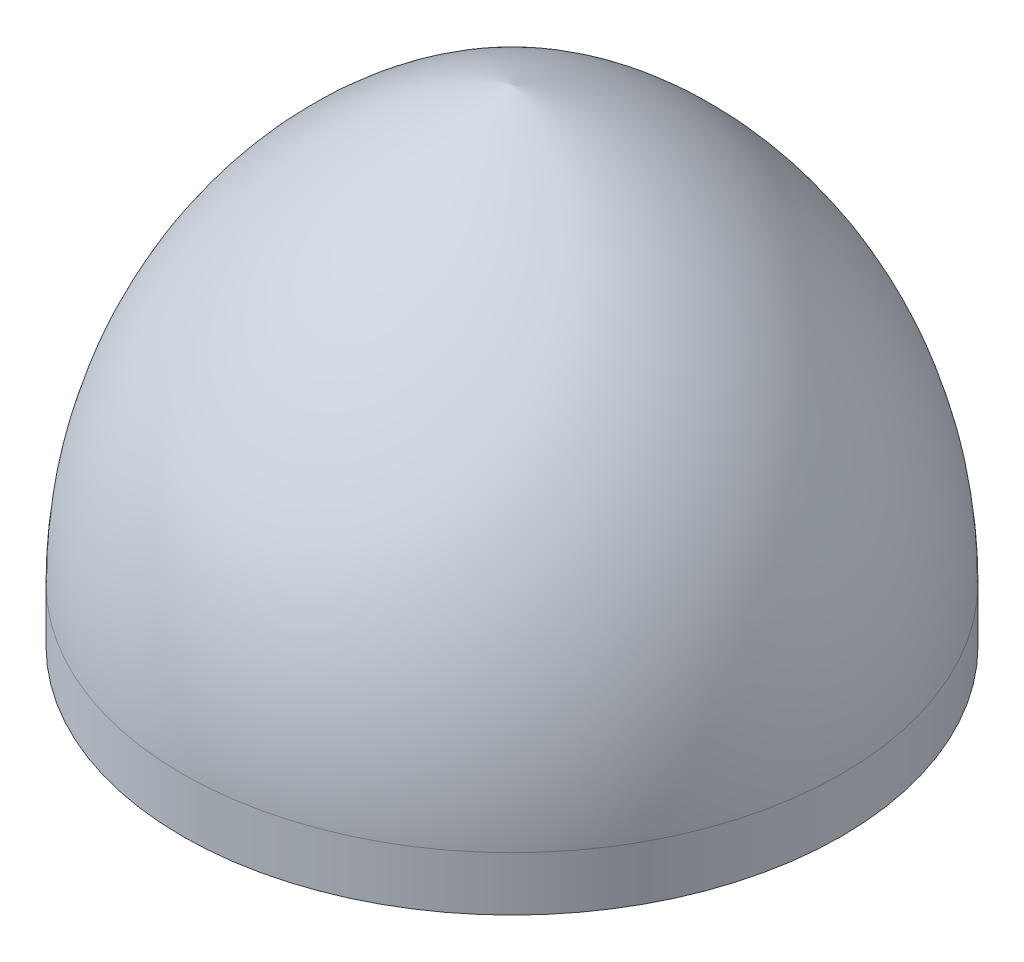
SolidWorks part; units mm, degrees
ref_plane "Front Plane" through (0, 0, 0) normal (0, 0, 1) x (1, 0, 0)
ref_plane "Top Plane" through (0, 0, 0) normal (0, 1, 0) x (1, 0, 0)
ref_plane "Right Plane" through (0, 0, 0) normal (1, 0, 0) x (0, 0, -1)
sketch "Sketch1" plane through (0, 0, 0) normal (0, 0, 1) x (1, 0, 0)
  line L1 (58, 170) -> (58, 160)
  line L4 (61, 170) -> (61, 160)
  line L5 (0, 246.8846) -> (0, 250)
  line L9 (58, 160) -> (61, 160)
  line L10 (0, 0) -> (0, 250) construction
  line L15 (58, 0) -> (58, 170) construction
  line L16 (61, 0) -> (61, 170) construction
  line L18 (58, 170) -> (55, 170)
  line L19 (58, 170) -> (58, 167)
  line L20 (58, 167) -> (55, 167)
  line L21 (55, 170) -> (55, 167)
  arc A0 (61, 170) -> (0, 250) centre (-21.959, 170) ccw
  arc A1 (58, 170) -> (0, 246.8846) centre (-21.959, 170) ccw
  arc A8 (58, 170) -> (-0.7941, 247.107) centre (-21.959, 170) ccw construction
  dimension "D1" = 3
  dimension "D2" = 170
  dimension "D3" = 80
  dimension "D8" = 10
  dimension "D5" = 61
  dimension "D4" = 3
revolve "Revolve7" add sketch "Sketch1" angle 360 about L10
sketch "Sketch2" plane through (0, 0, 0) normal (0, 0, 1) x (1, 0, 0)
  line L0 (61, 170) -> (55, 170)
  line L1 (61, 170) -> (-61, 170) construction
  line L2 (55, 170) -> (55, 167)
  line L3 (55, 167) -> (58, 167)
  line L4 (58, 167) -> (58, 170)
  line L5 (0, 250) -> (0, 160) construction
  line L6 (-61, 160) -> (61, 160) construction
  line L7 (-61, 170) -> (-55, 170)
  line L8 (-58, 167) -> (-58, 170)
  line L9 (-55, 170) -> (-55, 167)
  line L10 (-55, 167) -> (-58, 167)
  dimension "D1" = 6
  dimension "D2" = 3
revolve "Revolve8" add sketch "Sketch2" angle 3 about L5
sketch "Sketch3" plane through (0, 0, 0) normal (0, 0, 1) x (1, 0, 0)
  line L0 (61, 170) -> (52, 170)
  line L1 (61, 170) -> (-61, 170) construction
  line L2 (52, 170) -> (52, 167)
  line L3 (52, 167) -> (55, 167)
  line L4 (55, 167) -> (55, 170)
  line L5 (0, 250) -> (0, 160) construction
  line L6 (-61, 160) -> (61, 160) construction
  line L7 (-55, 167) -> (-55, 170)
  line L8 (-61, 170) -> (-52, 170)
  line L9 (-52, 170) -> (-52, 167)
  line L10 (-52, 167) -> (-55, 167)
  dimension "D1" = 9
  dimension "D2" = 3
  dimension "D3" = 3
revolve "Revolve9" add sketch "Sketch3" angle 10 about L5
